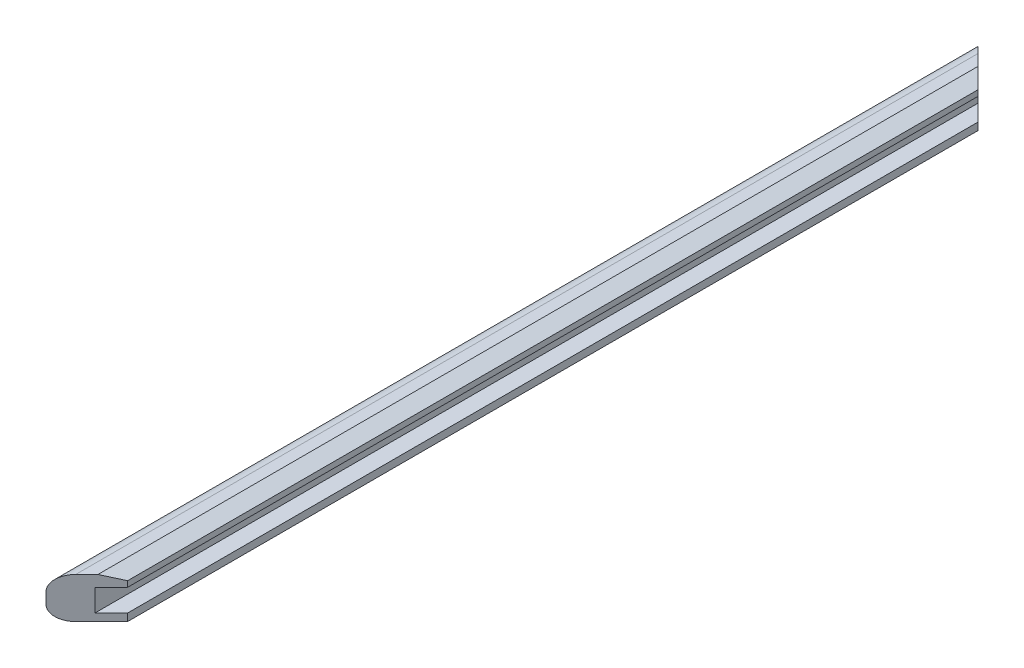
SolidWorks part; units mm, degrees
ref_plane "Front" through (0, 0, 0) normal (0, 0, 1) x (1, 0, 0)
ref_plane "Top" through (0, 0, 0) normal (0, 1, 0) x (1, 0, 0)
ref_plane "Right" through (0, 0, 0) normal (1, 0, 0) x (0, 0, -1)
sketch "Sketch1" plane through (0, 0, 0) normal (0, 0, 1) x (1, 0, 0)
  line L1 (-17.4625, -17.4625) -> (17.4625, -17.4625)
  line L2 (-17.4625, -17.4625) -> (-17.4625, 17.4625)
  line L3 (-17.4625, 17.4625) -> (17.4625, 17.4625)
  line L4 (17.4625, -17.4625) -> (17.4625, 17.4625)
  line L5 (-17.4625, -17.4625) -> (17.4625, 17.4625) construction
  line L6 (-17.4625, 17.4625) -> (17.4625, -17.4625) construction
  point P0 (0, 0)
  dimension "D1" = 34.925
extrude "Boss-Extrude1" add sketch "Sketch1" against normal blind 1320.8
sketch "Sketch2" plane through (0, 0, 0) normal (0, 0, 1) x (1, 0, 0)
  line L0 (17.4625, -17.4625) -> (17.4625, 17.4625) construction
  line L1 (17.4625, 7.9375) -> (3.4925, 7.9375)
  line L2 (17.4625, 7.9375) -> (17.4625, -11.1125)
  line L3 (17.4625, -11.1125) -> (3.4925, -11.1125)
  line L4 (3.4925, 7.9375) -> (3.4925, -11.1125)
  line L5 (17.4625, 17.4625) -> (-17.4625, 17.4625) construction
  dimension "D1" = 19.05
  dimension "D2" = 9.525
  dimension "D3" = 13.97
extrude "Cut-Extrude1" cut sketch "Sketch2" against normal through all
fillet "Fillet1" radius 12.7 2 edges at (-17.4625, -17.4625, -660.4) (-17.4625, 17.4625, -660.4)
chamfer "Chamfer1" distance 12.7 angle 20 1 edges at (17.4625, 17.4625, -660.4)
sketch "Sketch3" plane through (0, 17.4625, 0) normal (0, 1, 0) x (1, 0, 0)
  line L0 (-17.4625, 0) -> (17.4625, 34.925)
  line L2 (17.4625, 1320.8) -> (17.4625, 0) construction
  line L3 (17.4625, 34.925) -> (17.4625, 0)
  line L4 (17.4625, 0) -> (-17.4625, 0)
  line L5 (-17.4625, 797.56) -> (17.4625, 762.635)
  line L6 (-17.4625, 0) -> (-17.4625, 1320.8) construction
  line L7 (17.4625, 762.635) -> (-17.4625, 762.635) construction
  line L8 (-17.4625, 762.635) -> (-17.4625, 797.56) construction
  line L9 (-17.4625, 797.56) -> (-17.4625, 1320.8)
  line L10 (-17.4625, 1320.8) -> (17.4625, 1320.8)
  line L11 (17.4625, 1320.8) -> (17.4625, 762.635)
  line L12 (3.4925, 20.955) -> (3.4925, 776.605) construction
  line L13 (3.4925, 1320.8) -> (3.4925, 0) construction
  dimension "D1" = 45
  dimension "D2" = 45
  dimension "D3" = 755.65
extrude "Cut-Extrude2" cut sketch "Sketch3" against normal through all
